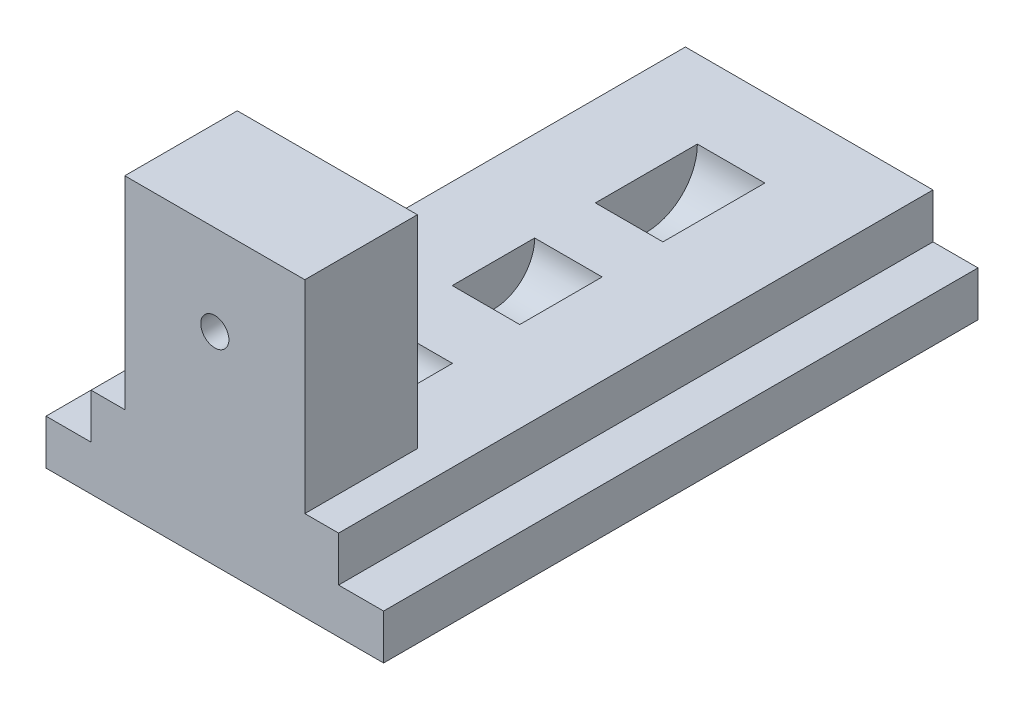
SolidWorks part; units mm, degrees
ref_plane "Спереди" through (0, 0, 0) normal (0, 0, 1) x (1, 0, 0)
ref_plane "Сверху" through (0, 0, 0) normal (0, 1, 0) x (1, 0, 0)
ref_plane "Справа" through (0, 0, 0) normal (1, 0, 0) x (0, 0, -1)
sketch "Эскиз1" plane through (0, 0, 0) normal (1, 0, 0) x (0, 0, -1)
  line L0 (0, 0) -> (52.8193, 0)
  line L1 (52.8193, 0) -> (52.8193, 8)
  line L2 (52.8193, 8) -> (45.8795, 8)
  line L3 (31.4217, 8) -> (36.8193, 8)
  line L4 (24.0964, 8) -> (18.1205, 8)
  line L5 (11.9518, 8) -> (0, 8)
  line L6 (0, 8) -> (0, 0)
  arc A0 (45.8795, 8) -> (36.8193, 8) centre (41.3494, 8) cw
  arc A1 (31.4217, 8) -> (24.0964, 8) centre (27.759, 8) cw
  arc A2 (18.1205, 8) -> (11.9518, 8) centre (15.0361, 8) cw
  dimension "D1" = 8
extrude "Бобышка-Вытянуть1" add sketch "Эскиз1" along normal blind 6
sketch "Эскиз2" plane through (0, 0, 0) normal (0, 0, 1) x (1, 0, 0)
  line L0 (6, 8) -> (14, 8)
  line L1 (14, 8) -> (14, 4)
  line L2 (18, 0) -> (6, 0)
  line L3 (6, 0) -> (6, 8)
  line L4 (14, 4) -> (18, 4)
  line L5 (18, 4) -> (18, 0)
  dimension "D1" = 8
  dimension "D2" = 4
  dimension "D3" = 4
extrude "Бобышка-Вытянуть2" add sketch "Эскиз2" against normal up to surface (52.8193 mm away) up to face at (3, 4, -52.8193)
sketch "Эскиз3" plane through (0, 0, 0) normal (0, 0, 1) x (1, 0, 0)
  line L0 (0, 8) -> (-8, 8)
  line L1 (-8, 8) -> (-8, 4)
  line L2 (-12, 0) -> (0, 0)
  line L3 (0, 0) -> (0, 8)
  line L4 (-8, 4) -> (-12, 4)
  line L5 (-12, 4) -> (-12, 0)
  dimension "D1" = 8
  dimension "D2" = 4
  dimension "D3" = 4
extrude "Бобышка-Вытянуть3" add sketch "Эскиз3" against normal up to surface (52.8193 mm away) up to face at (10.6667, 4, -52.8193)
sketch "Эскиз6" plane through (0, 8, 0) normal (0, 1, 0) x (1, 0, 0)
  line L0 (-5, 0) -> (-5, 10)
  line L1 (14, 0) -> (-8, 0) construction
  line L2 (-5, 10) -> (11, 10)
  line L3 (11, 10) -> (11, 0)
  line L4 (11, 0) -> (-5, 0)
  line L5 (3, 50.6635) -> (3, -6.4838) construction
  line L6 (14, 52.8193) -> (-8, 52.8193) construction
  point P10 (3, 52.8193)
  point P11 (3, 0)
  dimension "D1" = 16
  dimension "D2" = 10
extrude "Бобышка-Вытянуть5" add sketch "Эскиз6" along normal blind 18
sketch "Эскиз7" plane through (0, 0, 0) normal (0, 0, 1) x (1, 0, 0)
  line L0 (-5, 26) -> (11, 26) construction
  line L1 (-5, 26) -> (-5, 8) construction
  circle A0 centre (3, 18) radius 1.25
  dimension "D3" = 2.5
  dimension "D1" = 8
  dimension "D2" = 8
extrude "Вырез-Вытянуть2" cut sketch "Эскиз7" against normal up to surface (10 mm away) up to face at (3, 17, -10)
